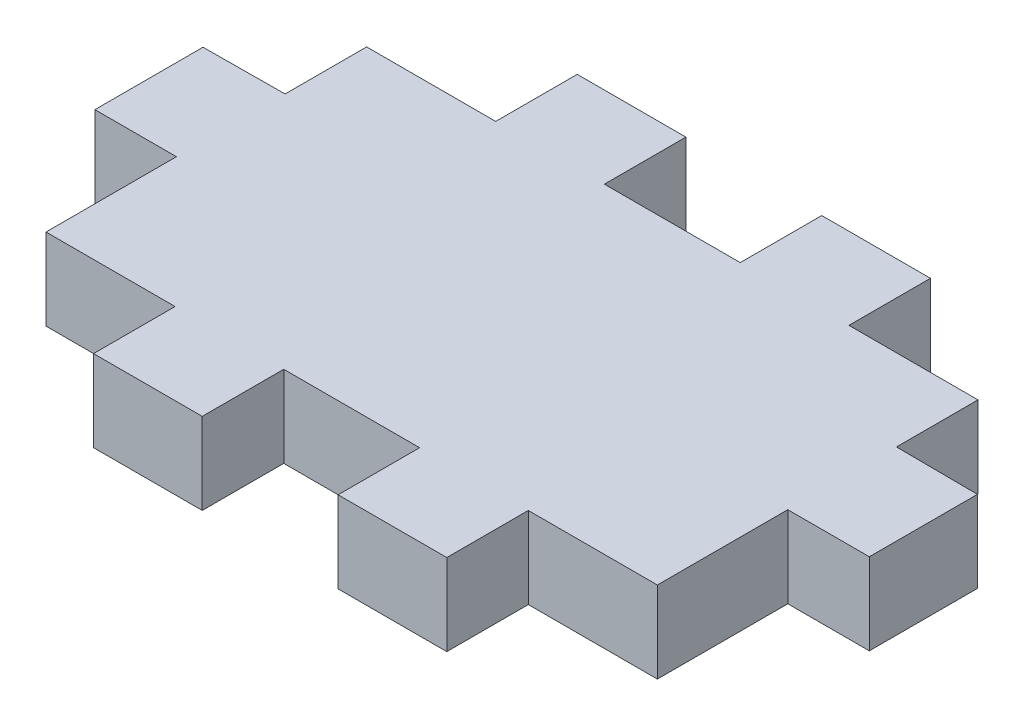
SolidWorks part; units mm, degrees
ref_plane "Front Plane" through (0, 0, 0) normal (0, 0, 1) x (1, 0, 0)
ref_plane "Top Plane" through (0, 0, 0) normal (0, 1, 0) x (1, 0, 0)
ref_plane "Right Plane" through (0, 0, 0) normal (1, 0, 0) x (0, 0, -1)
sketch "Sketch1" plane through (0, 0, 0) normal (0, 1, 0) x (1, 0, 0)
  line L1 (15, 25) -> (-15, 25)
  line L2 (15, 25) -> (15, -25)
  line L3 (15, -25) -> (-15, -25)
  line L4 (-15, 25) -> (-15, -25)
  line L5 (15, 25) -> (-15, -25) construction
  line L6 (15, -25) -> (-15, 25) construction
  point P0 (0, 0)
  dimension "D1" = 50
  dimension "D2" = 30
extrude "Boss-Extrude1" add sketch "Sketch1" along normal blind 3
sketch "Sketch2" plane through (0, 3, 0) normal (0, 1, 0) x (1, 0, 0)
  line L0 (15, 25) -> (-15, 25) construction
  line L1 (7.25, 22) -> (15, 22)
  line L2 (7.25, 22) -> (7.25, 25)
  line L3 (7.25, 25) -> (15, 25)
  line L4 (15, 22) -> (15, 25)
  line L5 (3.25, 22) -> (-1.75, 22)
  line L6 (3.25, 22) -> (3.25, 25)
  line L7 (3.25, 25) -> (-1.75, 25)
  line L8 (-1.75, 22) -> (-1.75, 25)
  line L11 (-5.75, 22) -> (-13.5, 22)
  line L12 (-5.75, 22) -> (-5.75, 25)
  line L13 (-5.75, 25) -> (-13.5, 25)
  line L14 (-13.5, 22) -> (-13.5, 25)
extrude "Cut-Extrude1" cut sketch "Sketch2" against normal blind 10
sketch "Sketch3" plane through (0, 3, 0) normal (0, 1, 0) x (1, 0, 0)
  line L0 (-13.5, 22) -> (-13.5, 7.2)
  line L1 (-13.5, 7.2) -> (33.8389, 7.2)
  line L2 (33.8389, 7.2) -> (23.9122, -42.1414)
  line L3 (23.9122, -42.1414) -> (-28.2264, -62.1514)
  line L4 (-28.2264, -62.1514) -> (-28.2264, 29.548)
  line L5 (-28.2264, 29.548) -> (-12.5453, 26.3932)
  line L6 (-12.5453, 26.3932) -> (-13.5, 22)
  line L7 (-1.75, 25) -> (-5.75, 25) construction
  dimension "D1" = 17.8
extrude "Cut-Extrude2" cut sketch "Sketch3" against normal blind 10
sketch "Sketch4" plane through (0, 3, 0) normal (0, 1, 0) x (1, 0, 0)
  line L0 (15, 7.2) -> (-13.5, 7.2) construction
  line L1 (7.25, 7.2) -> (15, 7.2)
  line L2 (7.25, 7.2) -> (7.25, 10.2)
  line L3 (7.25, 10.2) -> (15, 10.2)
  line L4 (15, 7.2) -> (15, 10.2)
  line L5 (15, 7.2) -> (15, 22) construction
  line L6 (-13.5, 7.2) -> (-13.5, 22) construction
  line L7 (-13.5, 10.2) -> (-5.75, 10.2)
  line L8 (-13.5, 10.2) -> (-13.5, 7.2)
  line L9 (-13.5, 7.2) -> (-5.75, 7.2)
  line L10 (-5.75, 10.2) -> (-5.75, 7.2)
  line L12 (-1.75, 10.2) -> (3.25, 10.2)
  line L13 (-1.75, 10.2) -> (-1.75, 7.2)
  line L14 (-1.75, 7.2) -> (3.25, 7.2)
  line L15 (3.25, 10.2) -> (3.25, 7.2)
  dimension "D1" = 3
  dimension "D2" = 3
  dimension "D3" = 3
  dimension "D4" = 7.75
  dimension "D5" = 7.75
  dimension "D6" = 4
  dimension "D7" = 4
extrude "Cut-Extrude3" cut sketch "Sketch4" against normal blind 10
sketch "Sketch5" plane through (0, 3, 0) normal (0, 1, 0) x (1, 0, 0)
  line L0 (-10.5, 10.2) -> (-10.5, 15)
  line L1 (-5.75, 10.2) -> (-13.5, 10.2) construction
  line L2 (-10.5, 15) -> (-10.5, 10.161) construction
  line L3 (-10.5, 15) -> (-13.5, 15)
  line L4 (-13.5, 10.2) -> (-13.5, 22) construction
  line L5 (-10.5, 15) -> (-13.5, 15) construction
  line L6 (-13.5, 15) -> (-13.5, 18.9776)
  line L7 (-13.5, 18.9776) -> (-10.5, 19)
  line L8 (-10.5, 19) -> (-10.5, 22)
  line L9 (-13.5, 22) -> (-5.75, 22) construction
  line L10 (-10.5, 22) -> (-10.5, 19) construction
  line L11 (-10.5, 22) -> (-14.4417, 22)
  line L12 (-14.4417, 22) -> (-14.4417, 10.2)
  line L13 (-14.4417, 10.2) -> (-10.5, 10.2)
  line L14 (0.75, 22) -> (0.75, 10.2) construction
  line L15 (-1.75, 22) -> (3.25, 22) construction
  line L16 (3.25, 10.2) -> (-1.75, 10.2) construction
  line L17 (15.9417, 22) -> (15.9417, 10.2)
  line L18 (12, 22) -> (15.9417, 22)
  line L19 (12, 19) -> (12, 22)
  line L20 (15, 18.9776) -> (12, 19)
  line L21 (15, 15) -> (15, 18.9776)
  line L22 (12, 15) -> (15, 15)
  line L23 (12, 10.2) -> (12, 15)
  line L24 (15.9417, 10.2) -> (12, 10.2)
extrude "Cut-Extrude4" cut sketch "Sketch5" against normal blind 3
